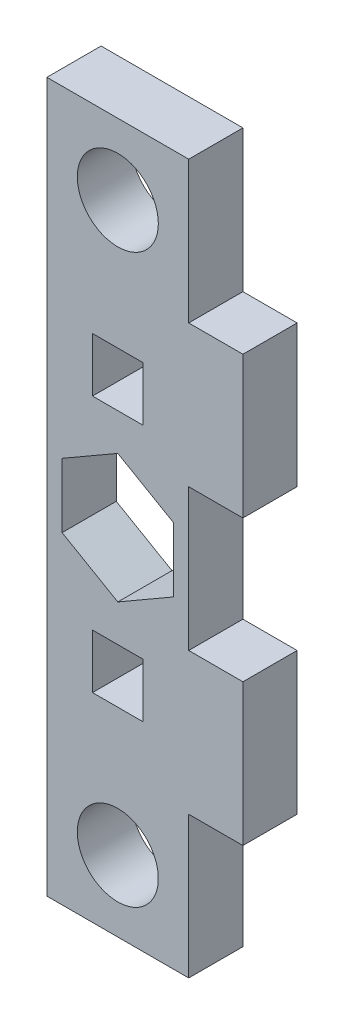
SolidWorks part; units mm, degrees
ref_plane "Front Plane" through (0, 0, 0) normal (0, 0, 1) x (1, 0, 0)
ref_plane "Top Plane" through (0, 0, 0) normal (0, 1, 0) x (1, 0, 0)
ref_plane "Right Plane" through (0, 0, 0) normal (1, 0, 0) x (0, 0, -1)
sketch "Model" plane through (0, 0, 0) normal (0, 0, 1) x (1, 0, 0)
  line L0 (7, 70) -> (7, 0) construction
  line L1 (0, 0) -> (14, 0)
  line L2 (0, 0) -> (0, 70)
  line L3 (0, 70) -> (14, 70)
  line L4 (14, 0) -> (14, 14)
  line L5 (0, 35) -> (14, 35) construction
  line L6 (14, 56) -> (14, 70)
  line L7 (4.5, 45) -> (9.5, 45)
  line L8 (4.5, 45) -> (4.5, 50.35)
  line L9 (4.5, 50.35) -> (9.5, 50.35)
  line L10 (9.5, 45) -> (9.5, 50.35)
  line L11 (4.5, 45) -> (9.5, 50.35) construction
  line L12 (4.5, 50.35) -> (9.5, 45) construction
  line L13 (14, 56) -> (19.35, 56)
  line L14 (19.35, 14) -> (19.35, 28)
  line L15 (14, 42) -> (19.35, 42)
  line L16 (19.35, 56) -> (19.35, 42)
  line L17 (14, 28) -> (19.35, 28)
  line L18 (14, 14) -> (19.35, 14)
  line L19 (4.5, 19.65) -> (9.5, 25) construction
  line L20 (4.5, 25) -> (9.5, 19.65) construction
  line L21 (9.5, 25) -> (9.5, 19.65)
  line L22 (4.5, 19.65) -> (9.5, 19.65)
  line L23 (4.5, 25) -> (4.5, 19.65)
  line L24 (4.5, 25) -> (9.5, 25)
  line L25 (14, 28) -> (14, 42)
  line L27 (1.5007, 38.175) -> (1.5007, 31.825)
  line L28 (1.5007, 31.825) -> (7, 28.65)
  line L29 (7, 28.65) -> (12.4993, 31.825)
  line L30 (12.4993, 31.825) -> (12.4993, 38.175)
  line L31 (12.4993, 38.175) -> (7, 41.35)
  line L32 (7, 41.35) -> (1.5007, 38.175)
  circle A0 centre (7, 63) radius 4
  circle A1 centre (7, 7) radius 4
  circle A2 centre (7, 35) radius 5.4993 construction
  point P10 (7, 47.675)
  point P29 (7, 22.325)
  dimension "D5" = 8
  dimension "D1" = 70
  dimension "D2" = 14
  dimension "D8" = 7
  dimension "D11" = 5
  dimension "D12" = 5.35
  dimension "D14" = 19.65
  dimension "D15" = 14
  dimension "D16" = 5.35
  dimension "D19" = 14
  dimension "D21" = 12.7
extrude "Boss-Extrude1" add sketch "Model" along normal blind 5.35
equation "\"mdfthick\"=5.35"
equation "\"D12@Model\"=\"mdfthick\""
equation "\"D16@Model\"=\"mdfthick\""
equation "\"D1@Boss-Extrude1\"=\"mdfthick\""
